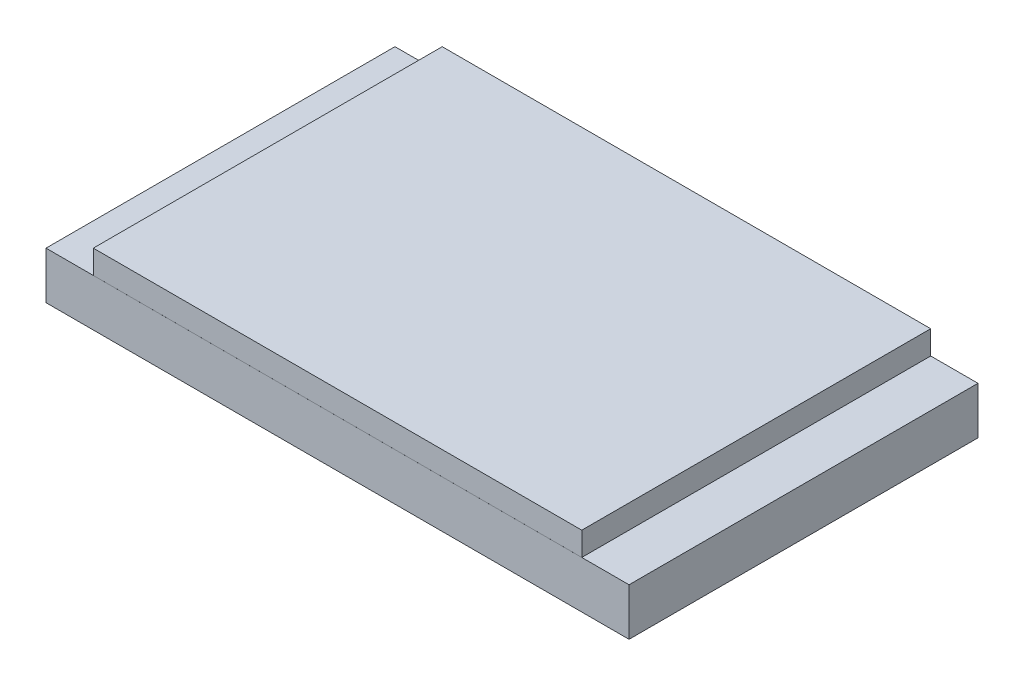
SolidWorks part; units mm, degrees
ref_plane "Front Plane" through (0, 0, 0) normal (0, 0, 1) x (1, 0, 0)
ref_plane "Top Plane" through (0, 0, 0) normal (0, 1, 0) x (1, 0, 0)
ref_plane "Right Plane" through (0, 0, 0) normal (1, 0, 0) x (0, 0, -1)
sketch "Sketch1" plane through (0, 0, 0) normal (0, 1, 0) x (1, 0, 0)
  line L1 (20.6688, -14.7635) -> (-20.6688, -14.7635)
  line L2 (20.6688, -14.7635) -> (20.6688, 14.7635)
  line L3 (20.6688, 14.7635) -> (-20.6688, 14.7635)
  line L4 (-20.6688, -14.7635) -> (-20.6688, 14.7635)
  line L5 (20.6688, -14.7635) -> (-20.6688, 14.7635) construction
  line L6 (20.6688, 14.7635) -> (-20.6688, -14.7635) construction
  point P0 (0, 0)
  dimension "D1" = 50.8
sketch "Sketch2" plane through (0, 0, 0) normal (0, 1, 0) x (1, 0, 0)
  line L1 (24.67, -14.765) -> (-24.67, -14.765)
  line L2 (24.67, -14.765) -> (24.67, 14.765)
  line L3 (24.67, 14.765) -> (-24.67, 14.765)
  line L4 (-24.67, -14.765) -> (-24.67, 14.765)
  line L5 (24.67, -14.765) -> (-24.67, 14.765) construction
  line L6 (24.67, 14.765) -> (-24.67, -14.765) construction
  point P0 (0, 0)
  dimension "D1" = 29.53
  dimension "D2" = 49.34
extrude "Boss-Extrude1" add sketch "Sketch1" along normal blind 2 from offset 2
extrude "Boss-Extrude2" add sketch "Sketch2" along normal blind 4 from offset 2
